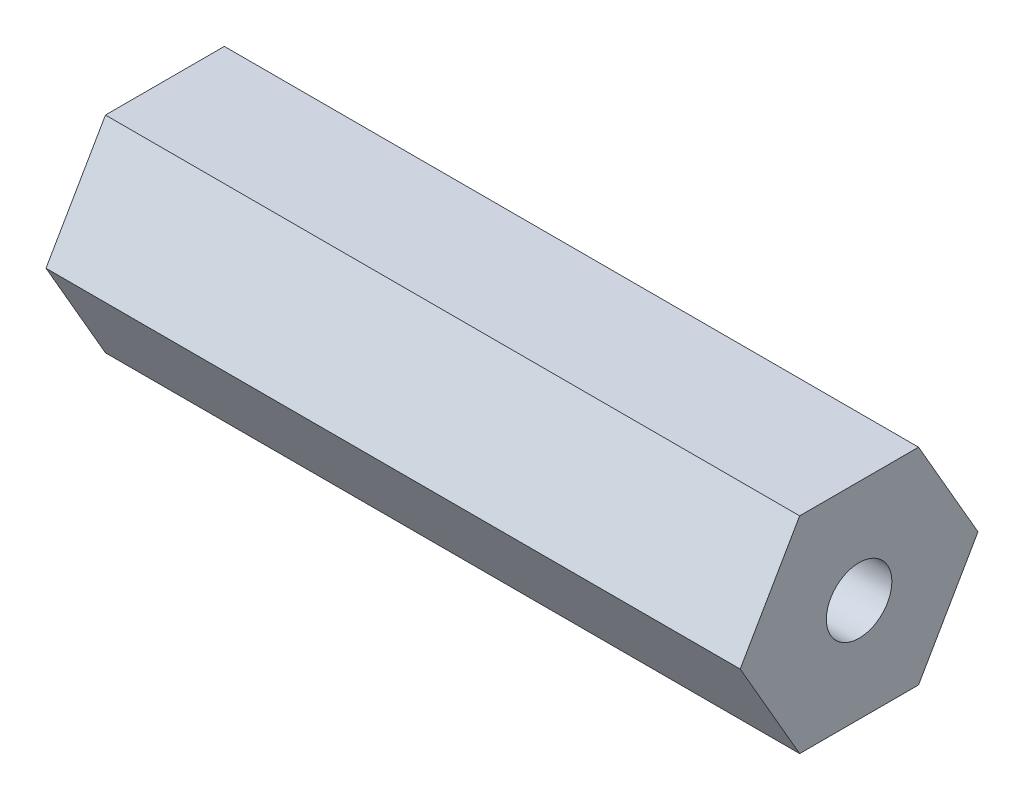
SolidWorks part; units mm, degrees
ref_plane "Front Plane" through (0, 0, 0) normal (0, 0, 1) x (1, 0, 0)
ref_plane "Top Plane" through (0, 0, 0) normal (0, 1, 0) x (1, 0, 0)
ref_plane "Right Plane" through (0, 0, 0) normal (1, 0, 0) x (0, 0, -1)
sketch "Sketch1" plane through (0, 0, 0) normal (1, 0, 0) x (0, 0, -1)
  line L1 (7.3323, 0) -> (3.6662, 6.35)
  line L2 (3.6662, 6.35) -> (-3.6662, 6.35)
  line L3 (-3.6662, 6.35) -> (-7.3323, 0)
  line L4 (-7.3323, 0) -> (-3.6662, -6.35)
  line L5 (-3.6662, -6.35) -> (3.6662, -6.35)
  line L6 (3.6662, -6.35) -> (7.3323, 0)
  circle A0 centre (0, 0) radius 6.35 construction
  circle A1 centre (0, 0) radius 2.0193
  dimension "D1" = 12.7
  dimension "D2" = 4.0386
extrude "Boss-Extrude1" add sketch "Sketch1" along normal blind 42.8117
